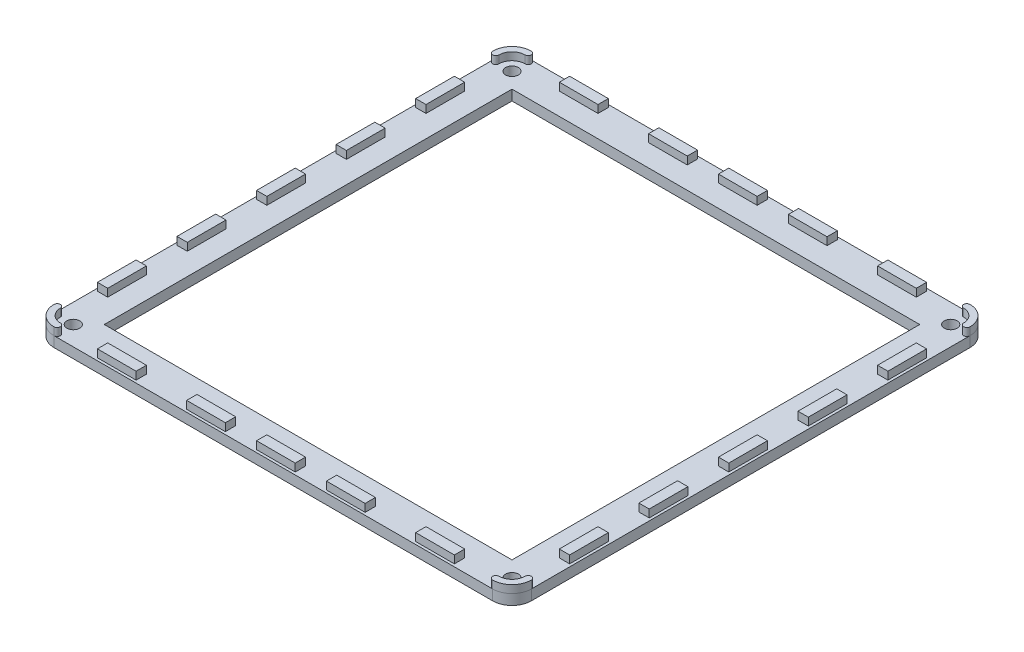
SolidWorks part; units mm, degrees
ref_plane "Alzado" through (0, 0, 0) normal (0, 0, 1) x (1, 0, 0)
ref_plane "Planta" through (0, 0, 0) normal (0, 1, 0) x (1, 0, 0)
ref_plane "Vista lateral" through (0, 0, 0) normal (1, 0, 0) x (0, 0, -1)
sketch "Croquis1" plane through (0, 0, 0) normal (0, 1, 0) x (1, 0, 0)
  line L0 (100, 15) -> (100, 0) construction
  line L1 (0, 0) -> (200, 0)
  line L2 (0, 0) -> (0, 200)
  line L3 (0, 200) -> (200, 200)
  line L4 (200, 0) -> (200, 200)
  line L5 (15, 15) -> (185, 15) construction
  line L6 (15, 15) -> (15, 185) construction
  line L7 (15, 185) -> (185, 185) construction
  line L8 (185, 15) -> (185, 185) construction
  line L9 (185, 100) -> (200, 100) construction
  circle A0 centre (15, 185) radius 2.5
  circle A1 centre (185, 185) radius 2.5
  circle A2 centre (185, 15) radius 2.5
  circle A3 centre (15, 15) radius 2.5
  dimension "D3" = 5
  dimension "D1" = 200
  dimension "D2" = 170
extrude "Saliente-Extruir1" add sketch "Croquis1" along normal blind 4
sketch "Croquis2" plane through (0, 4, 0) normal (0, 1, 0) x (1, 0, 0)
  line L0 (0, 200) -> (200, 0) construction
  line L2 (21, 21) -> (179, 21)
  line L3 (21, 21) -> (21, 179)
  line L4 (21, 179) -> (179, 179)
  line L5 (179, 21) -> (179, 179)
  line L6 (21, 21) -> (179, 179) construction
  line L7 (21, 179) -> (179, 21) construction
  point P4 (100, 100)
  dimension "D1" = 158
extrude "Cortar-Extruir1" cut sketch "Croquis2" against normal blind 10
sketch "Croquis4" plane through (0, 4, 0) normal (0, 1, 0) x (1, 0, 0)
  line L0 (21, 100) -> (0, 100) construction
  line L1 (21, 179) -> (21, 21) construction
  line L2 (0, 200) -> (0, 0) construction
  line L3 (10.5, 100) -> (10.5, 123.3333) construction
  line L4 (8.5, 123.3333) -> (12.5, 123.3333)
  line L5 (8.5, 123.3333) -> (8.5, 138.3333)
  line L6 (8.5, 138.3333) -> (12.5, 138.3333)
  line L7 (12.5, 123.3333) -> (12.5, 138.3333)
  line L8 (8.5, 154.1667) -> (12.5, 154.1667)
  line L9 (8.5, 154.1667) -> (8.5, 169.1667)
  line L10 (8.5, 169.1667) -> (12.5, 169.1667)
  line L11 (12.5, 154.1667) -> (12.5, 169.1667)
  line L12 (10.5, 123.3333) -> (10.5, 138.3333) construction
  line L13 (10.5, 138.3333) -> (10.5, 154.1667) construction
  line L14 (10.5, 154.1667) -> (10.5, 169.1667) construction
  line L15 (10.5, 169.1667) -> (10.5, 200) construction
  line L16 (200, 200) -> (0, 200) construction
  line L17 (100, 179) -> (100, 200) construction
  line L18 (191.5, 107.5) -> (191.5, 92.5)
  line L19 (100, 189.5) -> (80.4167, 189.5) construction
  line L20 (30.8333, 191.5) -> (45.8333, 191.5)
  line L21 (30.8333, 191.5) -> (30.8333, 187.5)
  line L22 (30.8333, 187.5) -> (45.8333, 187.5)
  line L23 (45.8333, 191.5) -> (45.8333, 187.5)
  line L24 (65.4167, 191.5) -> (80.4167, 191.5)
  line L25 (65.4167, 191.5) -> (65.4167, 187.5)
  line L26 (65.4167, 187.5) -> (80.4167, 187.5)
  line L27 (80.4167, 191.5) -> (80.4167, 187.5)
  line L28 (80.4167, 189.5) -> (65.4167, 189.5) construction
  line L29 (65.4167, 189.5) -> (45.8333, 189.5) construction
  line L30 (45.8333, 189.5) -> (30.8333, 189.5) construction
  line L31 (30.8333, 189.5) -> (0, 189.5) construction
  line L32 (10, 185) -> (7.5, 185) construction
  line L33 (15, 190) -> (15, 192.5) construction
  line L34 (21, 179) -> (179, 21) construction
  line L84 (8.5, 107.5) -> (12.5, 107.5)
  line L85 (8.5, 107.5) -> (8.5, 92.5)
  line L87 (12.5, 107.5) -> (12.5, 92.5)
  line L88 (8.5, 107.5) -> (10.5, 100) construction
  line L89 (10.5, 100) -> (12.5, 107.5) construction
  line L101 (0, 179) -> (21, 179) construction
  line L102 (21, 179) -> (21, 200) construction
  line L103 (15, 185) -> (0, 185) construction
  line L104 (12.5, 138.3333) -> (12.5, 154.1667) construction
  line L105 (12.5, 107.5) -> (12.5, 123.3333) construction
  line L106 (12.5, 169.1667) -> (12.5, 185) construction
  line L107 (191.5, 107.5) -> (187.5, 107.5)
  line L108 (179, 179) -> (21, 179) construction
  line L109 (187.5, 107.5) -> (187.5, 92.5)
  line L110 (107.5, 187.5) -> (92.5, 187.5)
  line L112 (107.5, 191.5) -> (92.5, 191.5)
  line L113 (92.5, 187.5) -> (92.5, 191.5)
  line L114 (191.5, 138.3333) -> (187.5, 138.3333)
  line L115 (187.5, 123.3333) -> (187.5, 138.3333)
  line L116 (191.5, 123.3333) -> (187.5, 123.3333)
  line L117 (191.5, 123.3333) -> (191.5, 138.3333)
  line L118 (191.5, 169.1667) -> (187.5, 169.1667)
  line L119 (187.5, 154.1667) -> (187.5, 169.1667)
  line L120 (191.5, 154.1667) -> (187.5, 154.1667)
  line L121 (191.5, 154.1667) -> (191.5, 169.1667)
  line L122 (169.1667, 187.5) -> (154.1667, 187.5)
  line L123 (154.1667, 191.5) -> (154.1667, 187.5)
  line L124 (169.1667, 191.5) -> (154.1667, 191.5)
  line L125 (169.1667, 191.5) -> (169.1667, 187.5)
  line L126 (134.5833, 187.5) -> (119.5833, 187.5)
  line L127 (119.5833, 191.5) -> (119.5833, 187.5)
  line L128 (134.5833, 191.5) -> (119.5833, 191.5)
  line L129 (134.5833, 191.5) -> (134.5833, 187.5)
  line L130 (107.5, 187.5) -> (107.5, 191.5)
  line L131 (8.5, 92.5) -> (12.5, 92.5)
  line L132 (8.5, 61.6667) -> (12.5, 61.6667)
  line L133 (12.5, 76.6667) -> (12.5, 61.6667)
  line L134 (8.5, 76.6667) -> (12.5, 76.6667)
  line L135 (8.5, 76.6667) -> (8.5, 61.6667)
  line L136 (8.5, 30.8333) -> (12.5, 30.8333)
  line L137 (12.5, 45.8333) -> (12.5, 30.8333)
  line L138 (8.5, 45.8333) -> (12.5, 45.8333)
  line L139 (8.5, 45.8333) -> (8.5, 30.8333)
  line L140 (30.8333, 12.5) -> (45.8333, 12.5)
  line L141 (45.8333, 8.5) -> (45.8333, 12.5)
  line L142 (30.8333, 8.5) -> (45.8333, 8.5)
  line L143 (30.8333, 8.5) -> (30.8333, 12.5)
  line L144 (65.4167, 12.5) -> (80.4167, 12.5)
  line L145 (80.4167, 8.5) -> (80.4167, 12.5)
  line L146 (65.4167, 8.5) -> (80.4167, 8.5)
  line L147 (65.4167, 8.5) -> (65.4167, 12.5)
  line L148 (107.5, 12.5) -> (92.5, 12.5)
  line L149 (92.5, 12.5) -> (92.5, 8.5)
  line L150 (107.5, 8.5) -> (92.5, 8.5)
  line L151 (107.5, 12.5) -> (107.5, 8.5)
  line L152 (134.5833, 8.5) -> (134.5833, 12.5)
  line L153 (134.5833, 8.5) -> (119.5833, 8.5)
  line L154 (119.5833, 8.5) -> (119.5833, 12.5)
  line L155 (134.5833, 12.5) -> (119.5833, 12.5)
  line L156 (169.1667, 8.5) -> (169.1667, 12.5)
  line L157 (169.1667, 8.5) -> (154.1667, 8.5)
  line L158 (154.1667, 8.5) -> (154.1667, 12.5)
  line L159 (169.1667, 12.5) -> (154.1667, 12.5)
  line L160 (191.5, 45.8333) -> (191.5, 30.8333)
  line L161 (191.5, 45.8333) -> (187.5, 45.8333)
  line L162 (187.5, 45.8333) -> (187.5, 30.8333)
  line L163 (191.5, 30.8333) -> (187.5, 30.8333)
  line L164 (191.5, 76.6667) -> (191.5, 61.6667)
  line L165 (191.5, 76.6667) -> (187.5, 76.6667)
  line L166 (187.5, 76.6667) -> (187.5, 61.6667)
  line L167 (191.5, 61.6667) -> (187.5, 61.6667)
  line L168 (191.5, 92.5) -> (187.5, 92.5)
  arc A0 (15, 192.5) -> (7.5, 185) centre (15, 185) ccw
  arc A1 (15, 190) -> (10, 185) centre (15, 185) ccw
  arc A2 (7.5, 185) -> (10, 185) centre (8.75, 185) ccw
  arc A3 (15, 190) -> (15, 192.5) centre (15, 191.25) ccw
  arc A4 (185, 192.5) -> (192.5, 185) centre (185, 185) cw
  arc A5 (185, 190) -> (185, 192.5) centre (185, 191.25) cw
  arc A6 (185, 190) -> (190, 185) centre (185, 185) cw
  arc A7 (192.5, 185) -> (190, 185) centre (191.25, 185) cw
  arc A8 (15, 7.5) -> (7.5, 15) centre (15, 15) cw
  arc A9 (15, 10) -> (15, 7.5) centre (15, 8.75) cw
  arc A10 (15, 10) -> (10, 15) centre (15, 15) cw
  arc A11 (7.5, 15) -> (10, 15) centre (8.75, 15) cw
  arc A12 (185, 10) -> (185, 7.5) centre (185, 8.75) ccw
  arc A13 (192.5, 15) -> (190, 15) centre (191.25, 15) ccw
  arc A14 (185, 10) -> (190, 15) centre (185, 15) ccw
  arc A15 (185, 7.5) -> (192.5, 15) centre (185, 15) ccw
  point P41 (100, 191.5)
  point P55 (0, 0)
  point P57 (100, 189.5)
  point P90 (100, 187.5)
  point P91 (8.5, 100)
  point P92 (12.5, 100)
  point P148 (187.5, 100)
  point P149 (191.5, 100)
  dimension "D4" = 10
  dimension "D5" = 2.5
  dimension "D1" = 15
  dimension "D2" = 4
  dimension "D3" = 7.5
  dimension "D6" = 7.5
extrude "Saliente-Extruir2" add sketch "Croquis4" along normal blind 3
sketch "Croquis5" plane through (0, 4, 0) normal (0, 1, 0) x (1, 0, 0)
  line L0 (200, 200) -> (0, 200) construction
  line L1 (200, 0) -> (200, 200) construction
  line L2 (0, 0) -> (200, 0) construction
  line L3 (0, 200) -> (0, 0) construction
  line L4 (200, 200) -> (0, 200)
  line L5 (200, 0) -> (200, 200)
  line L6 (0, 0) -> (200, 0)
  line L7 (0, 200) -> (0, 0)
  line L8 (192.5, 192.5) -> (7.5, 192.5)
  line L9 (7.5, 192.5) -> (7.5, 7.5)
  line L10 (7.5, 7.5) -> (192.5, 7.5)
  line L11 (192.5, 7.5) -> (192.5, 192.5)
  dimension "D1" = 7.5
extrude "Cortar-Extruir2" cut sketch "Croquis5" against normal blind 5
fillet "Redondeo1" radius 7.5 4 edges at (7.5, 2, -7.5) (7.5, 2, -192.5) (192.5, 2, -192.5) (192.5, 2, -7.5)
